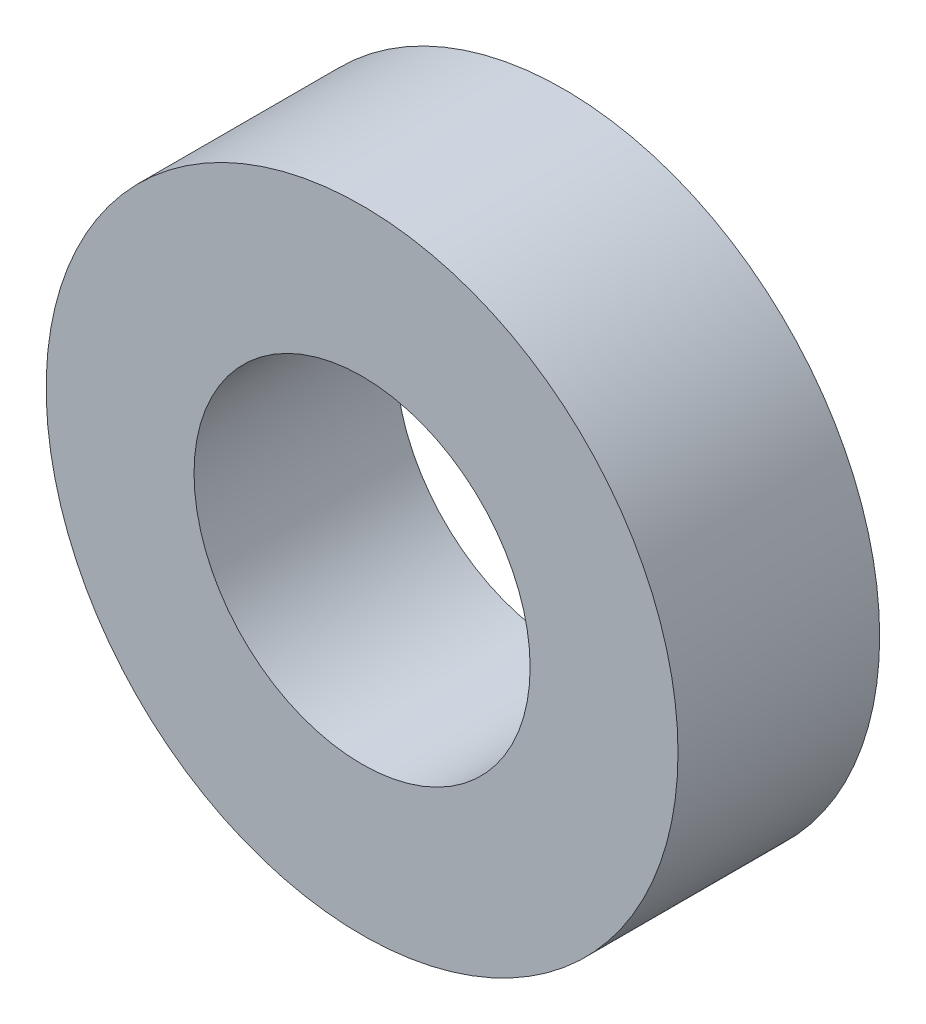
SolidWorks part; units mm, degrees
ref_plane "Front Plane" through (0, 0, 0) normal (0, 0, 1) x (1, 0, 0)
ref_plane "Top Plane" through (0, 0, 0) normal (0, 1, 0) x (1, 0, 0)
ref_plane "Right Plane" through (0, 0, 0) normal (1, 0, 0) x (0, 0, -1)
sketch "Sketch1" plane through (0, 0, 0) normal (0, 0, 1) x (1, 0, 0)
  circle A0 centre (0, 0) radius 23.5
  circle A1 centre (0, 0) radius 12.5
  dimension "D1" = 25
  dimension "D2" = 47
extrude "Boss-Extrude1" add sketch "Sketch1" along normal blind 15
